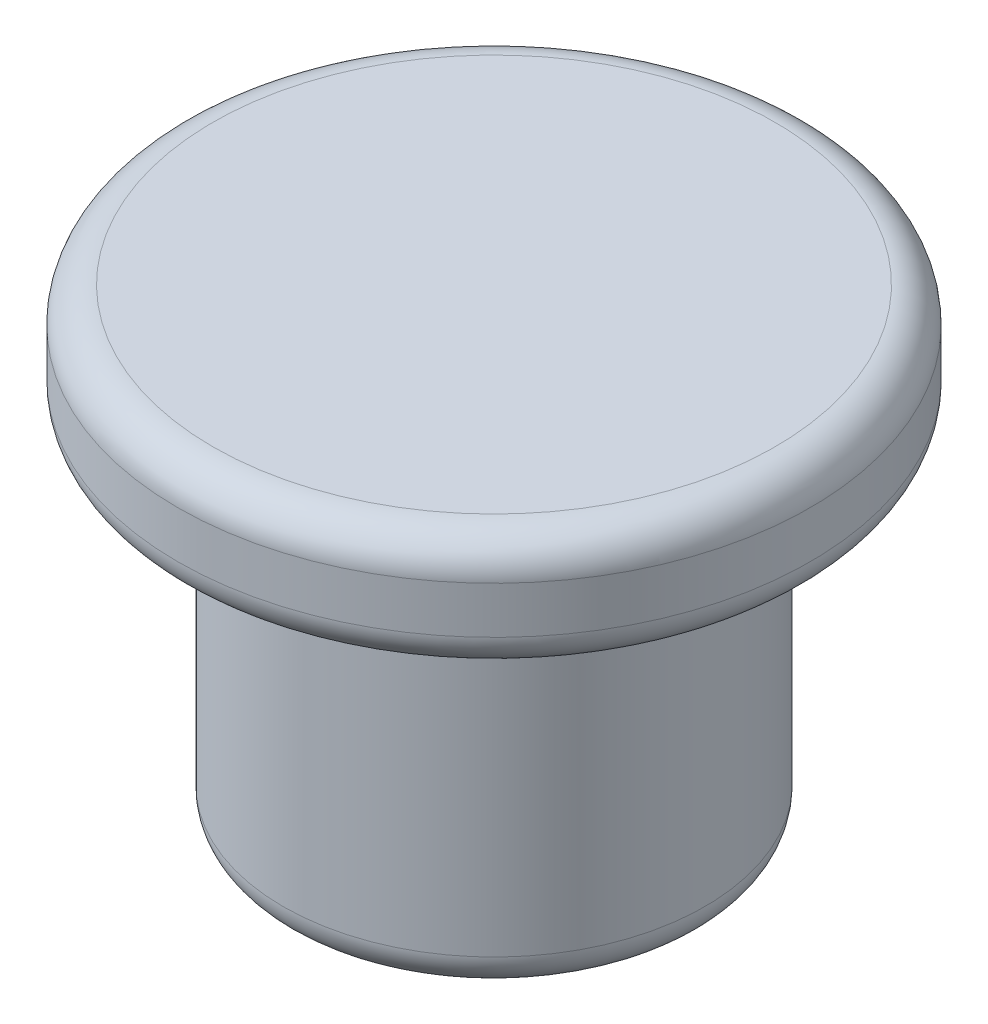
SolidWorks part; units mm, degrees
ref_plane "Front Plane" through (0, 0, 0) normal (0, 0, 1) x (1, 0, 0)
ref_plane "Top Plane" through (0, 0, 0) normal (0, 1, 0) x (1, 0, 0)
ref_plane "Right Plane" through (0, 0, 0) normal (1, 0, 0) x (0, 0, -1)
sketch "Sketch1" plane through (0, 0, 0) normal (0, 0, 1) x (1, 0, 0)
  line L0 (-1000, 0) -> (-14, 0) construction
  line L1 (0, 0) -> (0, -16963.4189) construction
  line L2 (-18, 0) -> (-18, 30)
  line L3 (-18, 30) -> (-27, 30)
  line L4 (-27, 30) -> (-27, 40)
  line L13 (-14, 0) -> (-18, 0)
  line L14 (-27, 40) -> (0, 40)
  line L15 (-14, 0) -> (-14, 30)
  line L16 (-14, 30) -> (0, 30)
  line L17 (0, 40) -> (0, 30)
  dimension "D1" = 54
  dimension "D2" = 36
  dimension "D3" = 28
  dimension "D4" = 10
  dimension "D5" = 30
revolve "Revolve1" add sketch "Sketch1" angle 360 about L1
fillet "Fillet1" radius 3 5 edges at (0, 40, 27) (0, 30, 14) (0, 0, 18) (0, 30, 18) (0, 30, 27)
